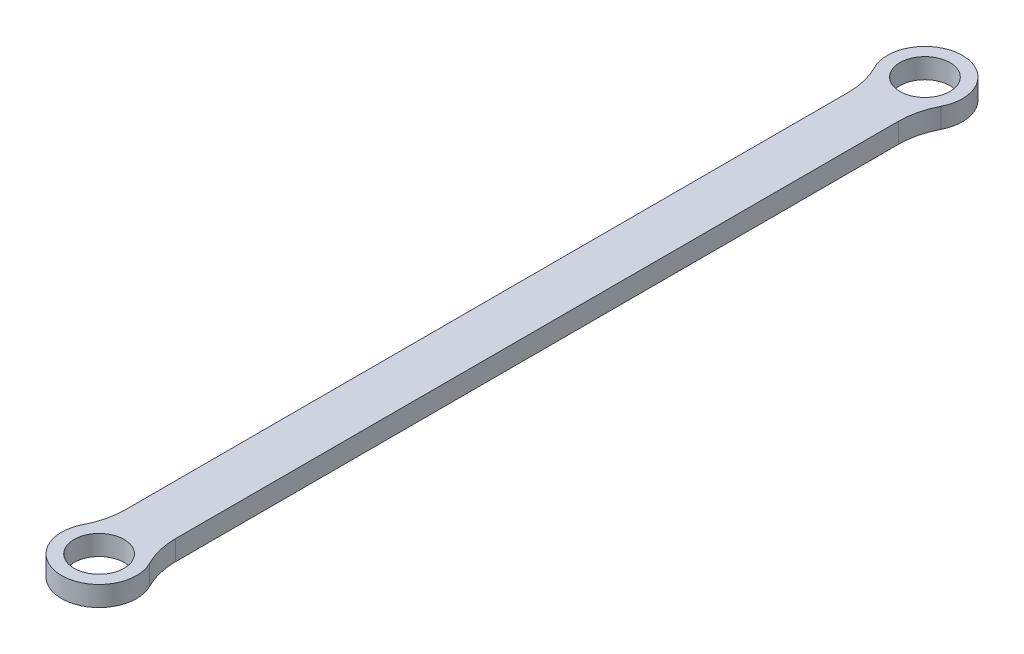
SolidWorks part; units mm, degrees
ref_plane "Front Plane" through (0, 0, 0) normal (0, 0, 1) x (1, 0, 0)
ref_plane "Top Plane" through (0, 0, 0) normal (0, 1, 0) x (1, 0, 0)
ref_plane "Right Plane" through (0, 0, 0) normal (1, 0, 0) x (0, 0, -1)
sketch "Sketch1" plane through (0, 0, 0) normal (0, 1, 0) x (1, 0, 0)
  line L1 (-5, -82.5) -> (5, -82.5)
  line L2 (-5, -82.5) -> (-5, 82.5)
  line L3 (-5, 82.5) -> (5, 82.5)
  line L4 (5, -82.5) -> (5, 82.5)
  line L5 (-5, -82.5) -> (5, 82.5) construction
  line L6 (-5, 82.5) -> (5, -82.5) construction
  circle A0 centre (0, 82.5) radius 5
  circle A1 centre (0, -82.5) radius 5
  circle A2 centre (0, 82.5) radius 7.5
  circle A3 centre (0, -82.5) radius 7.5
  point P0 (0, 0)
  dimension "D2" = 15
  dimension "D3" = 15
  dimension "D5" = 10
  dimension "D1" = 165
  dimension "D4" = 10
extrude "Boss-Extrude1" add sketch "Sketch1" along normal blind 4 contours L2 A3 L4 A1 | L4 A3 L2 A1 | A3 L4 A2 L2 | L3 A0 | L3 A0
fillet "Fillet1" radius 15 4 edges at (-5, 2, -76.9098) (5, 2, -76.9098) (5, 2, 76.9098) (-5, 2, 76.9098)
